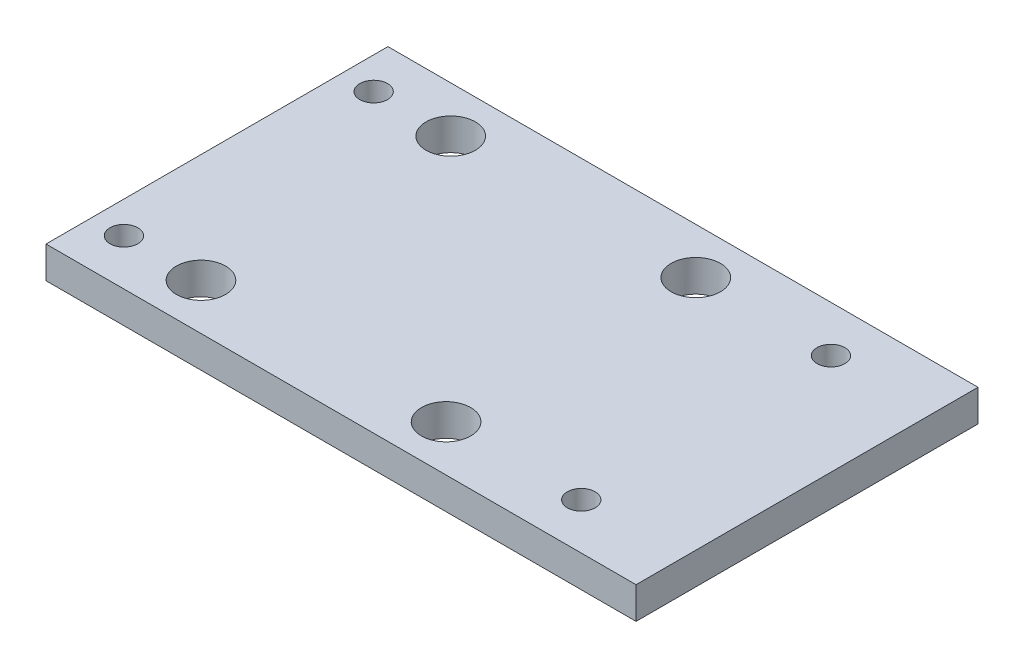
SolidWorks part; units mm, degrees
ref_plane "Front Plane" through (0, 0, 0) normal (0, 0, 1) x (1, 0, 0)
ref_plane "Top Plane" through (0, 0, 0) normal (0, 1, 0) x (1, 0, 0)
ref_plane "Right Plane" through (0, 0, 0) normal (1, 0, 0) x (0, 0, -1)
sketch "Sketch1" plane through (0, 0, 0) normal (0, 0, 1) x (1, 0, 0)
  line L1 (0, 0) -> (20, 0)
  line L3 (0, 20) -> (20, 20)
  line L4 (20, 0) -> (20, 20)
  line L6 (-50.2, 29) -> (-42.2, 29) construction
  line L11 (24, 33) -> (24, -13)
  line L12 (-42.2, -9) -> (0, -9)
  line L13 (-42.2, 29) -> (0, 29)
  line L15 (-50.2, 33) -> (-50.2, -13)
  line L16 (-50.2, 33) -> (24, 33)
  line L17 (-50.2, -13) -> (24, -13)
  line L18 (0, 29) -> (0, 20)
  line L21 (0, 0) -> (0, -9)
  line L22 (-42.2, -9) -> (-50.2, -8.4) construction
  line L24 (-42.2, 29) -> (-42.2, -9)
  dimension "D1" = 20
  dimension "D2" = 20
  dimension "D3" = 4
  dimension "D4" = 9
  dimension "D5" = 4
  dimension "D6" = 42.2
  dimension "D7" = 37.4
  dimension "D8" = 8
  dimension "D9" = 4
  dimension "D10" = 9
  dimension "D11" = 20
extrude "Boss-Extrude1" add sketch "Sketch1" along normal blind 43
sketch "Sketch2" plane through (0, -13, 0) normal (0, -1, 0) x (1, 0, 0)
  line L0 (0, 0) -> (-42.2, 43) construction
  line L1 (0, 0) -> (0, 43) construction
  line L2 (-50.2, 43) -> (24, 43) construction
  line L3 (0, 43) -> (-42.2, 0) construction
  line L4 (-36.5096, 37.2017) -> (-36.5096, 5.7983) construction
  line L5 (-5.6904, 5.7983) -> (-5.6904, 37.2017) construction
  line L6 (-42.2, 43) -> (-42.2, 0) construction
  line L7 (-50.2, 0) -> (24, 0) construction
  line L8 (-50.2, 43) -> (-50.2, 0) construction
  line L9 (20, 43) -> (20, 0) construction
  line L10 (24, 43) -> (24, 0) construction
  line L11 (0, 37.2017) -> (20, 37.2017) construction
  line L12 (0, 5.7983) -> (20, 5.7983) construction
  circle A0 centre (-21.1, 21.5) radius 11.5
  circle A1 centre (-36.5096, 37.2017) radius 1.75
  circle A2 centre (-5.6904, 5.7983) radius 1.75
  circle A3 centre (-36.5096, 5.7983) radius 1.75
  circle A4 centre (-5.6904, 37.2017) radius 1.75
  circle A7 centre (10, 37.2017) radius 2.5
  circle A8 centre (10, 5.7983) radius 2.5
  point P11 (-36.5096, 37.2017)
  point P12 (-5.6904, 5.7983)
  dimension "D1" = 23
  dimension "D4" = 3.5
  dimension "D5" = 3.5
  dimension "D6" = 3.5
  dimension "D7" = 3.5
  dimension "D9" = 4
  dimension "D10" = 5
  dimension "D11" = 5
  dimension "D2" = 22
  dimension "D3" = 22
  dimension "D8" = 8
extrude "Cut-Extrude1" cut sketch "Sketch2" against normal blind 20
sketch "Sketch3" plane through (0, 33, 0) normal (0, 1, 0) x (1, 0, 0)
  line L0 (0, 0) -> (0, -43) construction
  line L1 (24, -43) -> (-50.2, -43) construction
  line L2 (-42.2, 0) -> (0, -43) construction
  line L3 (0, 0) -> (-42.2, -43) construction
  line L4 (-36.5096, -5.7983) -> (-36.5096, -37.2017) construction
  line L5 (-36.5096, -37.2017) -> (-5.6904, -37.2017) construction
  line L6 (-5.6904, -5.7983) -> (-5.6904, -37.2017) construction
  line L7 (-36.5096, -5.7983) -> (-5.6904, -5.7983) construction
  line L8 (-42.2, 0) -> (-42.2, -43) construction
  line L9 (24, 0) -> (-50.2, 0) construction
  line L10 (-50.2, -43) -> (-50.2, 0) construction
  line L11 (-42.2, -5.7983) -> (-50.2, -5.7983) construction
  line L12 (-42.2, -37.2017) -> (-50.2, -37.2017) construction
  line L13 (0, -5.7983) -> (24, -5.7983) construction
  line L14 (24, -43) -> (24, 0) construction
  line L15 (0, -37.2017) -> (24, -37.2017) construction
  line L16 (11.3096, -5.7983) -> (11.3096, -37.2017) construction
  circle A0 centre (-36.5096, -5.7983) radius 3.1
  circle A1 centre (-5.6904, -5.7983) radius 3.1
  circle A2 centre (-5.6904, -37.2017) radius 3.1
  circle A3 centre (-36.5096, -37.2017) radius 3.1
  circle A4 centre (-46.2, -5.7983) radius 1.75
  circle A5 centre (-46.2, -37.2017) radius 1.75
  circle A6 centre (11.3096, -5.7983) radius 1.75
  circle A7 centre (11.3096, -37.2017) radius 1.75
  point P8 (-36.5096, -5.7983)
  point P10 (-21.1, -21.5)
  dimension "D2" = 6.2
  dimension "D3" = 6.2
  dimension "D4" = 6.2
  dimension "D5" = 6.2
  dimension "D7" = 3.5
  dimension "D8" = 3.5
  dimension "D9" = 3.5
  dimension "D10" = 3.5
  dimension "D1" = 22
  dimension "D6" = 8
  dimension "D11" = 17
extrude "Cut-Extrude2" cut sketch "Sketch3" against normal blind 15
ref_plane "Plane1" through (0, 29, 0) normal (0, 1, 0) x (1, 0, 0)
split "Split1" trim tools "Plane1" bodies to split 103 resulting bodies 106 107
sketch "Sketch4" plane through (0, 29, 0) normal (0, 1, 0) x (1, 0, 0)
  line L1 (-46.2, -2.3342) -> (-49.2, -4.0662)
  line L2 (-49.2, -4.0662) -> (-49.2, -7.5303)
  line L3 (-49.2, -7.5303) -> (-46.2, -9.2624)
  line L4 (-46.2, -9.2624) -> (-43.2, -7.5303)
  line L5 (-43.2, -7.5303) -> (-43.2, -4.0662)
  line L6 (-43.2, -4.0662) -> (-46.2, -2.3342)
  line L7 (-43.2, -35.4697) -> (-46.2, -33.7376)
  line L8 (-46.2, -33.7376) -> (-49.2, -35.4697)
  line L9 (-49.2, -35.4697) -> (-49.2, -38.9338)
  line L10 (-49.2, -38.9338) -> (-46.2, -40.6658)
  line L11 (-46.2, -40.6658) -> (-43.2, -38.9338)
  line L12 (-43.2, -38.9338) -> (-43.2, -35.4697)
  line L13 (14.3096, -4.0662) -> (11.3096, -2.3342)
  line L14 (11.3096, -2.3342) -> (8.3096, -4.0662)
  line L15 (8.3096, -4.0662) -> (8.3096, -7.5303)
  line L16 (8.3096, -7.5303) -> (11.3096, -9.2624)
  line L17 (11.3096, -9.2624) -> (14.3096, -7.5303)
  line L18 (14.3096, -7.5303) -> (14.3096, -4.0662)
  line L19 (14.3096, -35.4697) -> (11.3096, -33.7376)
  line L20 (11.3096, -33.7376) -> (8.3096, -35.4697)
  line L21 (8.3096, -35.4697) -> (8.3096, -38.9338)
  line L22 (8.3096, -38.9338) -> (11.3096, -40.6658)
  line L23 (11.3096, -40.6658) -> (14.3096, -38.9338)
  line L24 (14.3096, -38.9338) -> (14.3096, -35.4697)
  circle A0 centre (-46.2, -5.7983) radius 3 construction
  circle A1 centre (-46.2, -37.2017) radius 3 construction
  circle A2 centre (11.3096, -5.7983) radius 3 construction
  circle A3 centre (11.3096, -37.2017) radius 3 construction
  point P10 (-47.7, -39.7998)
  point P29 (9.8096, -8.3964)
  dimension "D1" = 6
  dimension "D2" = 6
  dimension "D3" = 6
  dimension "D4" = 6
extrude "Cut-Extrude3" cut sketch "Sketch4" against normal blind 2.4
sketch "Sketch5" plane through (24, 0, 0) normal (1, 0, 0) x (0, 0, -1)
  line L0 (0, 0) -> (-43, 0) construction
  line L1 (-43, -13) -> (-43, 29) construction
  line L2 (-43, 20) -> (0, 20) construction
  line L3 (0, -13) -> (0, 29) construction
  line L4 (-21.5, 20) -> (-21.5, 0) construction
  line L5 (-43, 10) -> (0, 10) construction
  circle A0 centre (-35.5, 10) radius 2.75
  circle A1 centre (-7.5, 10) radius 2.75
  point P17 (-21.5, 10)
  dimension "D2" = 5.5
  dimension "D3" = 5.5
  dimension "D1" = 20
extrude "Cut-Extrude4" cut sketch "Sketch5" against normal blind 12.4
delete or keep bodies "Body-Delete/Keep 1" type delete bodies bodies 109
